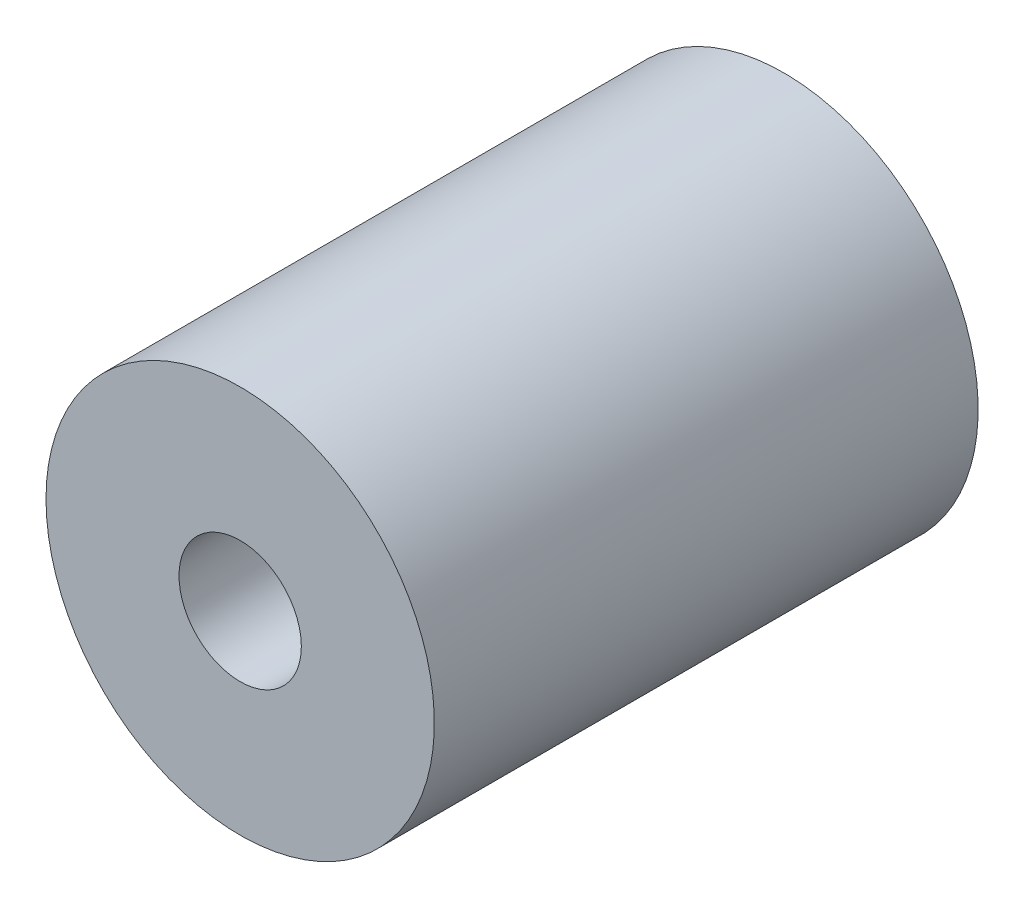
SolidWorks part; units mm, degrees
ref_plane "Front Plane" through (0, 0, 0) normal (0, 0, 1) x (1, 0, 0)
ref_plane "Top Plane" through (0, 0, 0) normal (0, 1, 0) x (1, 0, 0)
ref_plane "Right Plane" through (0, 0, 0) normal (1, 0, 0) x (0, 0, -1)
sketch "Sketch1" plane through (0, 0, 0) normal (0, 0, 1) x (1, 0, 0)
  circle A0 centre (0, 0) radius 9.525
  dimension "D1" = 19.05
extrude "Boss-Extrude1" add sketch "Sketch1" along a picked direction on the side of the normal blind 26.675 contours A0
sketch "Sketch2" plane through (0, 0, 26.675) normal (0, 0, 1) x (1, 0, 0)
  circle A0 centre (0, 0) radius 3
  dimension "D1" = 6
extrude "Cut-Extrude1" cut sketch "Sketch2" against normal through all
